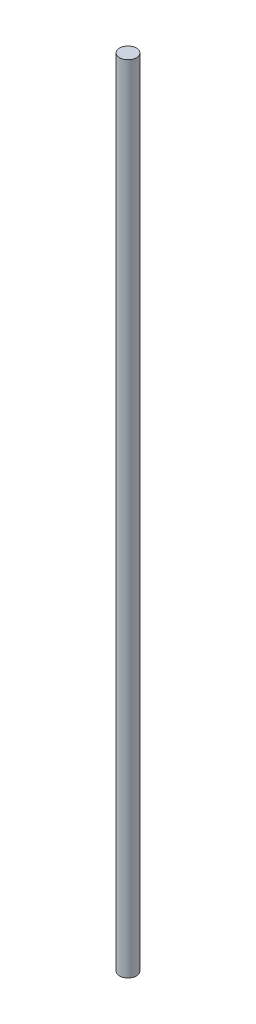
SolidWorks part; units mm, degrees
ref_plane "Front Plane" through (0, 0, 0) normal (0, 0, 1) x (1, 0, 0)
ref_plane "Top Plane" through (0, 0, 0) normal (0, 1, 0) x (1, 0, 0)
ref_plane "Right Plane" through (0, 0, 0) normal (1, 0, 0) x (0, 0, -1)
sketch "Sketch1" plane through (0, 0, 0) normal (0, 1, 0) x (1, 0, 0)
  circle A0 centre (0, 0) radius 3.175
  dimension "D1" = 6.35
extrude "Boss-Extrude1" add sketch "Sketch1" along normal blind 300
